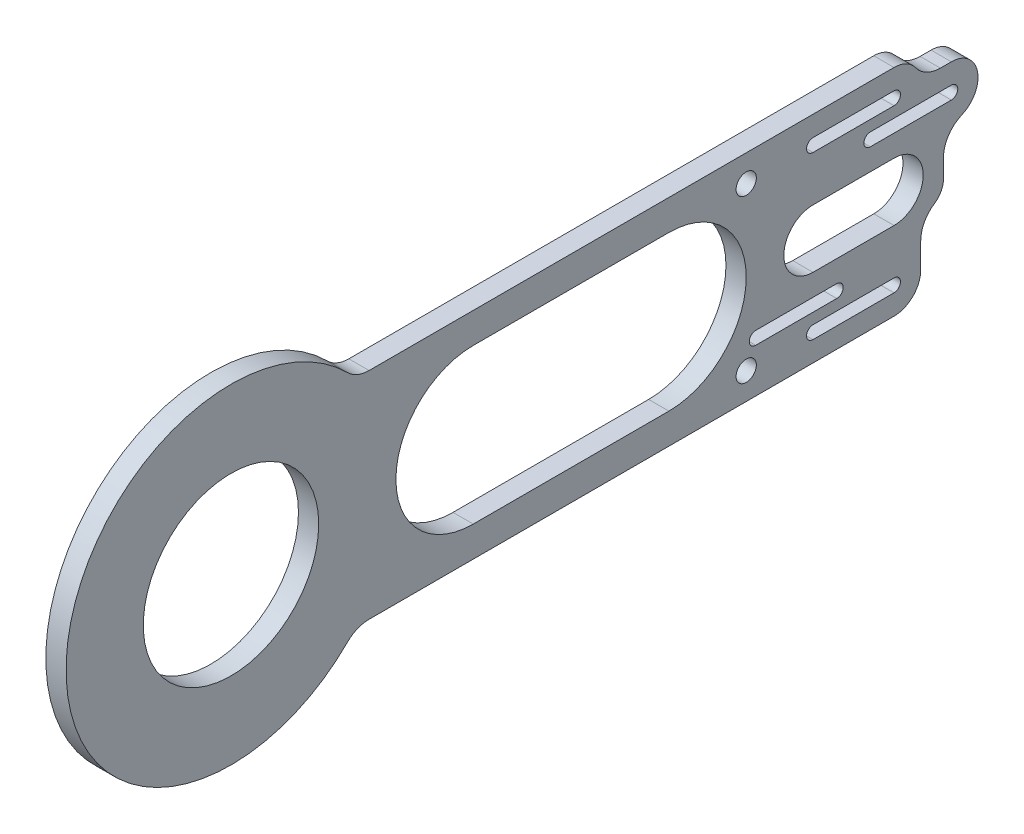
SolidWorks part; units mm, degrees
ref_plane "Front Plane" through (0, 0, 0) normal (0, 0, 1) x (1, 0, 0)
ref_plane "Top Plane" through (0, 0, 0) normal (0, 1, 0) x (1, 0, 0)
ref_plane "Right Plane" through (0, 0, 0) normal (1, 0, 0) x (0, 0, -1)
sketch "Sketch1" plane through (0, 0, 0) normal (1, 0, 0) x (0, 0, -1)
  line L0 (187, 0) -> (0, 0) construction
  line L6 (75.9443, 0) -> (137.2679, 0) construction
  line L7 (75.9443, 24.2443) -> (137.2679, 24.2443)
  line L8 (75.9443, -24.2443) -> (137.2679, -24.2443)
  line L9 (43.2909, 33.7693) -> (207.851, 33.7693)
  line L11 (75.9443, -33.7693) -> (137.2679, -33.7693) construction
  line L12 (75.9443, 33.7693) -> (137.2679, 33.7693) construction
  line L20 (-18.3858, -33.3131) -> (-15.1304, -28.413) construction
  line L21 (182.451, -25.4) -> (207.851, -25.4) construction
  line L22 (164.4904, -17.9605) -> (189.8904, -17.9605) construction
  line L23 (182.451, 25.4) -> (207.851, 25.4) construction
  line L24 (200.4115, 17.9605) -> (225.8115, 17.9605) construction
  line L25 (182.451, 0) -> (207.851, 0) construction
  line L26 (182.451, 0) -> (207.851, 0) construction
  line L27 (182.451, 9.144) -> (207.851, 9.144)
  line L28 (182.451, -9.144) -> (207.851, -9.144)
  line L29 (164.4904, -17.9605) -> (189.8904, -17.9605) construction
  line L30 (164.4904, -15.9412) -> (189.8904, -15.9412)
  line L31 (164.4904, -19.9798) -> (189.8904, -19.9798)
  line L32 (200.4115, 17.9605) -> (225.8115, 17.9605) construction
  line L33 (200.4115, 19.9798) -> (225.8115, 19.9798)
  line L34 (200.4115, 15.9412) -> (225.8115, 15.9412)
  line L35 (182.451, 25.4) -> (207.851, 25.4) construction
  line L36 (182.451, 27.4193) -> (207.851, 27.4193)
  line L37 (182.451, 23.3807) -> (207.851, 23.3807)
  line L38 (182.451, -25.4) -> (207.851, -25.4) construction
  line L39 (182.451, -23.3807) -> (207.851, -23.3807)
  line L40 (182.451, -27.4193) -> (207.851, -27.4193)
  line L41 (164.4904, -9.5912) -> (189.8904, -9.5912) construction
  line L42 (164.4904, -26.3298) -> (189.8904, -26.3298) construction
  line L43 (200.4115, 26.3298) -> (216.1684, 26.3298) construction
  line L44 (200.4115, 9.5912) -> (225.8115, 9.5912) construction
  line L45 (182.451, 33.7693) -> (207.851, 33.7693) construction
  line L46 (182.451, 17.0307) -> (207.851, 17.0307) construction
  line L47 (182.451, -17.0307) -> (207.851, -17.0307) construction
  line L48 (182.451, -33.7693) -> (207.851, -33.7693) construction
  line L49 (222.3734, 26.3298) -> (225.8115, 26.3298)
  line L50 (200.4115, 26.3298) -> (225.8115, 26.3298) construction
  line L51 (182.451, 15.494) -> (207.851, 15.494) construction
  line L52 (182.451, -15.494) -> (207.851, -15.494) construction
  line L53 (223.345, 1.5172) -> (223.345, -4.2399)
  line L54 (161.5122, 25.4) -> (161.5122, -25.4) construction
  line L55 (216.2203, -17.4855) -> (216.2203, -25.4)
  line L60 (20.3279, 24.96) -> (20.1161, 24.6412) construction
  line L61 (24.1108, 30.654) -> (23.5833, 29.8601) construction
  line L62 (20.3279, 24.96) -> (23.5833, 29.8601) construction
  line L63 (16.8544, 19.7315) -> (20.1161, 24.6412) construction
  line L64 (16.8544, 19.7315) -> (16.3247, 18.9342) construction
  line L65 (-28.9641, -26.2854) -> (-36.093, -37.016) construction
  line L66 (-28.9641, -26.2854) -> (-25.7087, -21.3853) construction
  line L69 (20.3279, 24.96) -> (20.1161, 24.6412) construction
  line L70 (24.1108, 30.654) -> (23.5833, 29.8601) construction
  line L71 (20.3279, 24.96) -> (23.5833, 29.8601) construction
  line L72 (16.8544, 19.7315) -> (20.1161, 24.6412) construction
  line L73 (16.8544, 19.7315) -> (16.3247, 18.9342) construction
  line L84 (43.2909, -33.7693) -> (207.851, -33.7693)
  line L85 (6.276, 26.7592) -> (9.5378, 31.6689) construction
  line L86 (9.7496, 31.9877) -> (13.005, 36.8879) construction
  line L87 (9.7496, 31.9877) -> (9.5378, 31.6689) construction
  line L88 (6.276, 26.7592) -> (5.7464, 25.9619) construction
  line L89 (20.1339, 47.6185) -> (13.005, 36.8879) construction
  line L90 (-18.3858, -33.3131) -> (-18.9132, -34.107) construction
  circle A0 centre (0, 0) radius 27.5
  arc A9 (195.151, -23.3807) -> (195.151, -27.4193) centre (195.151, -25.4) ccw construction
  arc A10 (195.151, -23.3807) -> (195.151, -27.4193) centre (195.151, -25.4) ccw construction
  arc A11 (195.151, -27.4193) -> (195.151, -23.3807) centre (195.151, -25.4) ccw construction
  arc A14 (195.151, -33.7693) -> (195.151, -17.0307) centre (195.151, -25.4) ccw construction
  arc A15 (195.151, -17.0307) -> (195.151, -33.7693) centre (195.151, -25.4) ccw construction
  arc A16 (207.851, -33.7693) -> (207.851, -17.0307) centre (207.851, -25.4) ccw construction
  arc A18 (195.151, -27.4193) -> (195.151, -23.3807) centre (195.151, -25.4) ccw construction
  arc A21 (213.1115, 19.9798) -> (213.1115, 15.9412) centre (213.1115, 17.9605) ccw construction
  arc A23 (177.1904, -15.9412) -> (177.1904, -19.9798) centre (177.1904, -17.9605) ccw construction
  arc A24 (177.1904, -19.9798) -> (177.1904, -15.9412) centre (177.1904, -17.9605) ccw construction
  arc A31 (213.1115, 19.9798) -> (213.1115, 15.9412) centre (213.1115, 17.9605) ccw construction
  arc A33 (177.1904, -15.9412) -> (177.1904, -19.9798) centre (177.1904, -17.9605) ccw construction
  arc A34 (177.1904, -19.9798) -> (177.1904, -15.9412) centre (177.1904, -17.9605) ccw construction
  arc A53 (75.9443, 24.2443) -> (75.9443, -24.2443) centre (75.9443, 0) ccw
  arc A55 (137.2679, -24.2443) -> (137.2679, 24.2443) centre (137.2679, 0) ccw
  arc A69 (75.9443, 33.7693) -> (75.9443, -33.7693) centre (75.9443, 0) ccw construction
  arc A71 (137.2679, -33.7693) -> (137.2679, 33.7693) centre (137.2679, 0) ccw construction
  arc A73 (195.151, 23.3807) -> (195.151, 27.4193) centre (195.151, 25.4) ccw construction
  arc A75 (195.151, 27.4193) -> (195.151, 23.3807) centre (195.151, 25.4) ccw construction
  arc A78 (195.151, 23.3807) -> (195.151, 27.4193) centre (195.151, 25.4) ccw construction
  arc A82 (195.151, 27.4193) -> (195.151, 23.3807) centre (195.151, 25.4) ccw construction
  arc A84 (195.3496, 9.1418) -> (194.9523, -9.1418) centre (195.151, 0) ccw construction
  arc A86 (194.9523, -9.1418) -> (195.3496, 9.1418) centre (195.151, 0) ccw construction
  arc A89 (43.2909, -33.7693) -> (36.556, -36.5588) centre (43.2909, -43.2943) ccw
  arc A90 (-18.9132, -34.107) -> (24.1108, 30.654) centre (0, 0) ccw construction
  arc A91 (-36.093, -37.016) -> (20.1339, 47.6185) centre (0, 0) ccw construction
  arc A93 (195.3496, 9.1418) -> (194.9523, -9.1418) centre (195.151, 0) ccw construction
  arc A94 (194.9523, -9.1418) -> (195.3496, 9.1418) centre (195.151, 0) ccw construction
  arc A95 (213.1115, 15.9412) -> (213.1115, 19.9798) centre (213.1115, 17.9605) ccw construction
  arc A100 (213.1115, 15.9412) -> (213.1115, 19.9798) centre (213.1115, 17.9605) ccw construction
  arc A101 (182.451, 9.144) -> (182.451, -9.144) centre (182.451, 0) ccw
  arc A102 (207.851, -9.144) -> (207.851, 9.144) centre (207.851, 0) ccw
  arc A103 (164.4904, -15.9412) -> (164.4904, -19.9798) centre (164.4904, -17.9605) ccw
  arc A104 (189.8904, -19.9798) -> (189.8904, -15.9412) centre (189.8904, -17.9605) ccw
  arc A105 (200.4115, 19.9798) -> (200.4115, 15.9412) centre (200.4115, 17.9605) ccw
  arc A106 (225.8115, 15.9412) -> (225.8115, 19.9798) centre (225.8115, 17.9605) ccw
  arc A107 (182.451, 27.4193) -> (182.451, 23.3807) centre (182.451, 25.4) ccw
  arc A108 (207.851, 23.3807) -> (207.851, 27.4193) centre (207.851, 25.4) ccw
  arc A109 (182.451, -23.3807) -> (182.451, -27.4193) centre (182.451, -25.4) ccw
  arc A110 (207.851, -27.4193) -> (207.851, -23.3807) centre (207.851, -25.4) ccw
  arc A111 (189.8904, -26.3298) -> (189.8904, -9.5912) centre (189.8904, -17.9605) ccw construction
  arc A112 (164.4904, -9.5912) -> (164.4904, -26.3298) centre (164.4904, -17.9605) ccw construction
  arc A113 (229.1128, 10.2698) -> (225.8115, 26.3298) centre (225.8115, 17.9605) ccw
  arc A114 (200.4115, 26.3298) -> (200.4115, 9.5912) centre (200.4115, 17.9605) ccw construction
  arc A115 (207.851, 17.0307) -> (216.1684, 26.3298) centre (207.851, 25.4) ccw construction
  arc A116 (182.451, 33.7693) -> (182.451, 17.0307) centre (182.451, 25.4) ccw construction
  arc A117 (207.851, -33.7693) -> (216.2203, -25.4) centre (207.851, -25.4) ccw
  arc A118 (182.451, -17.0307) -> (182.451, -33.7693) centre (182.451, -25.4) ccw construction
  arc A119 (214.6432, 30.2898) -> (222.3734, 26.3298) centre (222.3734, 35.8548) ccw
  arc A120 (214.6432, 30.2898) -> (207.851, 33.7693) centre (207.851, 25.4) ccw
  arc A121 (207.851, 17.0307) -> (207.851, 33.7693) centre (207.851, 25.4) ccw construction
  arc A122 (207.851, -15.494) -> (207.851, 15.494) centre (207.851, 0) ccw construction
  arc A123 (182.451, 15.494) -> (182.451, -15.494) centre (182.451, 0) ccw construction
  arc A124 (229.1128, 10.2698) -> (223.345, 1.5172) centre (232.87, 1.5172) ccw
  arc A125 (220.4951, -9.5381) -> (216.2203, -17.4855) centre (225.7453, -17.4855) ccw
  arc A126 (223.345, -4.2399) -> (220.4951, -9.5381) centre (216.995, -4.2399) cw
  circle A127 centre (161.5122, 25.4) radius 3.175
  circle A128 centre (161.5122, -25.4) radius 3.175
  circle A129 centre (161.5122, 25.4) radius 5.715 construction
  circle A130 centre (161.5122, -25.4) radius 5.715 construction
  arc A131 (-18.9132, -34.107) -> (24.1108, 30.654) centre (0, 0) ccw construction
  circle A132 centre (0, 0) radius 39 construction
  arc A133 (36.556, 36.5588) -> (36.556, -36.5588) centre (0, 0) ccw
  arc A134 (43.2909, 33.7693) -> (36.556, 36.5588) centre (43.2909, 43.2943) cw
  arc A135 (225.8115, 9.5912) -> (225.8115, 26.3298) centre (225.8115, 17.9605) ccw construction
  point P0 (39, 0)
  point P26 (177.1904, -17.9605)
  point P32 (195.151, 0)
  point P35 (195.151, -25.4)
  point P37 (0, 0)
  point P41 (195.151, 25.4)
  point P44 (213.1115, 17.9605)
  point P51 (195.151, 0)
  point P58 (177.1904, -17.9605)
  point P64 (161.5122, 0)
  point P67 (213.1115, 17.9605)
  point P76 (27.5, 0)
  point P82 (106.6061, 0)
  point P100 (195.151, 25.4)
  point P111 (195.151, -25.4)
  point P121 (51.7, 0)
  point P178 (161.5122, 0)
  dimension "D1" = 55
  dimension "D3" = 25.4
  dimension "D5" = 6.35
  dimension "D6" = 9.525
  dimension "D8" = 12.7
  dimension "D9" = 9.525
  dimension "D14" = 6.35
  dimension "D15" = 2.54
  dimension "D7" = 9.525
  dimension "D10" = 6.35
  dimension "D11" = 6.35
  dimension "D2" = 187
  dimension "D16" = 50.8
  dimension "D4" = 6.35
  dimension "D13" = 9.525
  dimension "D19" = 12.7
extrude "Boss-Extrude1" add sketch "Sketch1" along normal mid plane 6.35
